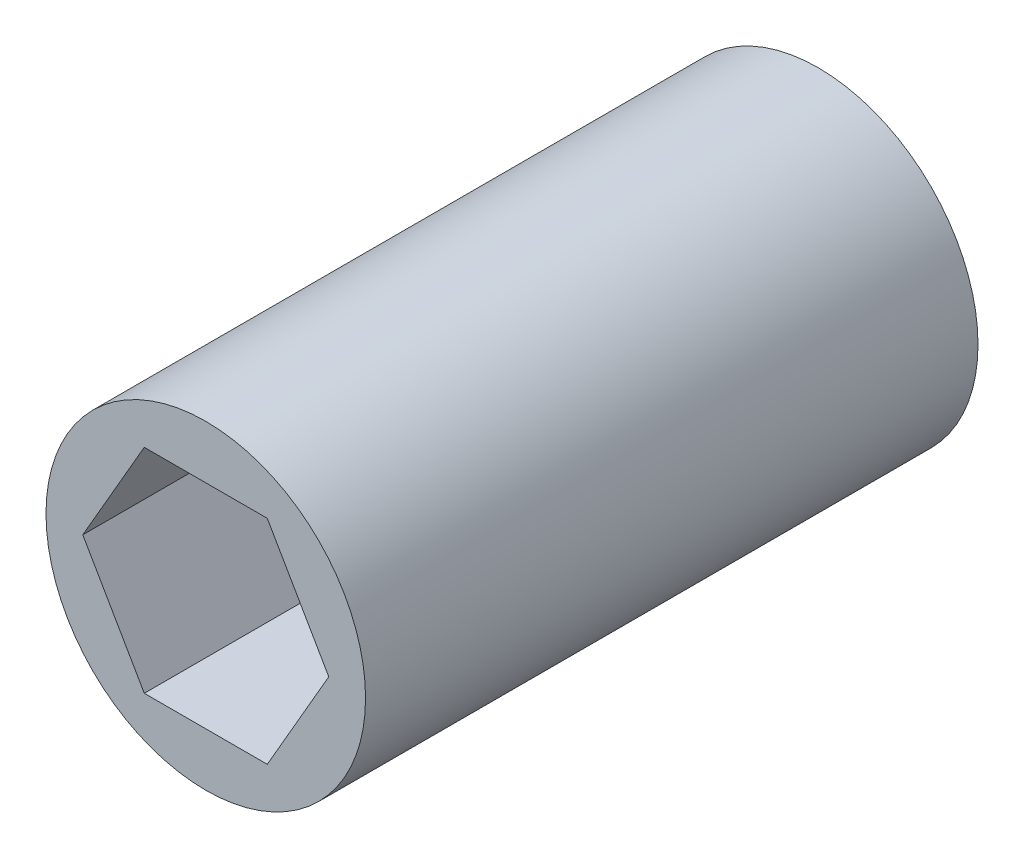
SolidWorks part; units mm, degrees
ref_plane "Front Plane" through (0, 0, 0) normal (0, 0, 1) x (1, 0, 0)
ref_plane "Top Plane" through (0, 0, 0) normal (0, 1, 0) x (1, 0, 0)
ref_plane "Right Plane" through (0, 0, 0) normal (1, 0, 0) x (0, 0, -1)
sketch "Sketch1" plane through (0, 0, 0) normal (0, 0, 1) x (1, 0, 0)
  line L1 (7.3323, 0) -> (3.6662, 6.35)
  line L2 (3.6662, 6.35) -> (-3.6662, 6.35)
  line L3 (-3.6662, 6.35) -> (-7.3323, 0)
  line L4 (-7.3323, 0) -> (-3.6662, -6.35)
  line L5 (-3.6662, -6.35) -> (3.6662, -6.35)
  line L6 (3.6662, -6.35) -> (7.3323, 0)
  circle A0 centre (0, 0) radius 6.35 construction
  circle A1 centre (0, 0) radius 9.525
  dimension "D2" = 19.05
  dimension "D1" = 12.7
extrude "Boss-Extrude1" add sketch "Sketch1" along normal mid plane 36.5125
